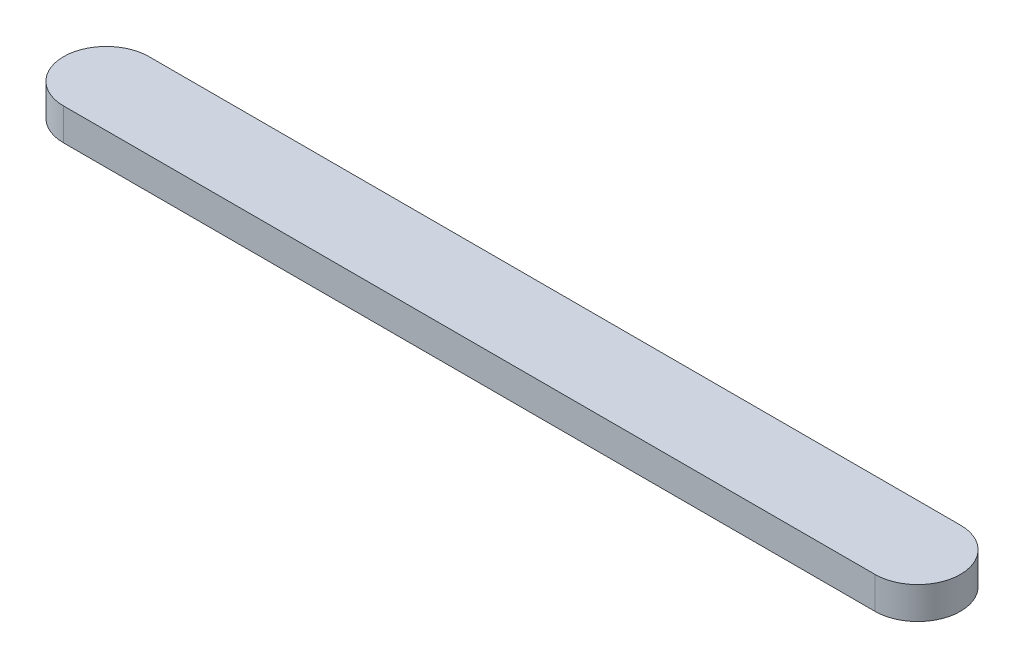
SolidWorks part; units mm, degrees
ref_plane "Front Plane" through (0, 0, 0) normal (0, 0, 1) x (1, 0, 0)
ref_plane "Top Plane" through (0, 0, 0) normal (0, 1, 0) x (1, 0, 0)
ref_plane "Right Plane" through (0, 0, 0) normal (1, 0, 0) x (0, 0, -1)
sketch "Sketch1" plane through (0, 0, 0) normal (0, 1, 0) x (1, 0, 0)
  line L0 (0, 0) -> (76, 0) construction
  line L1 (0, 4) -> (76, 4)
  line L2 (0, -4) -> (76, -4)
  arc A0 (0, 4) -> (0, -4) centre (0, 0) ccw
  arc A1 (76, -4) -> (76, 4) centre (76, 0) ccw
  point P3 (38, 0)
extrude "Boss-Extrude1" add sketch "Sketch1" along normal blind 3
